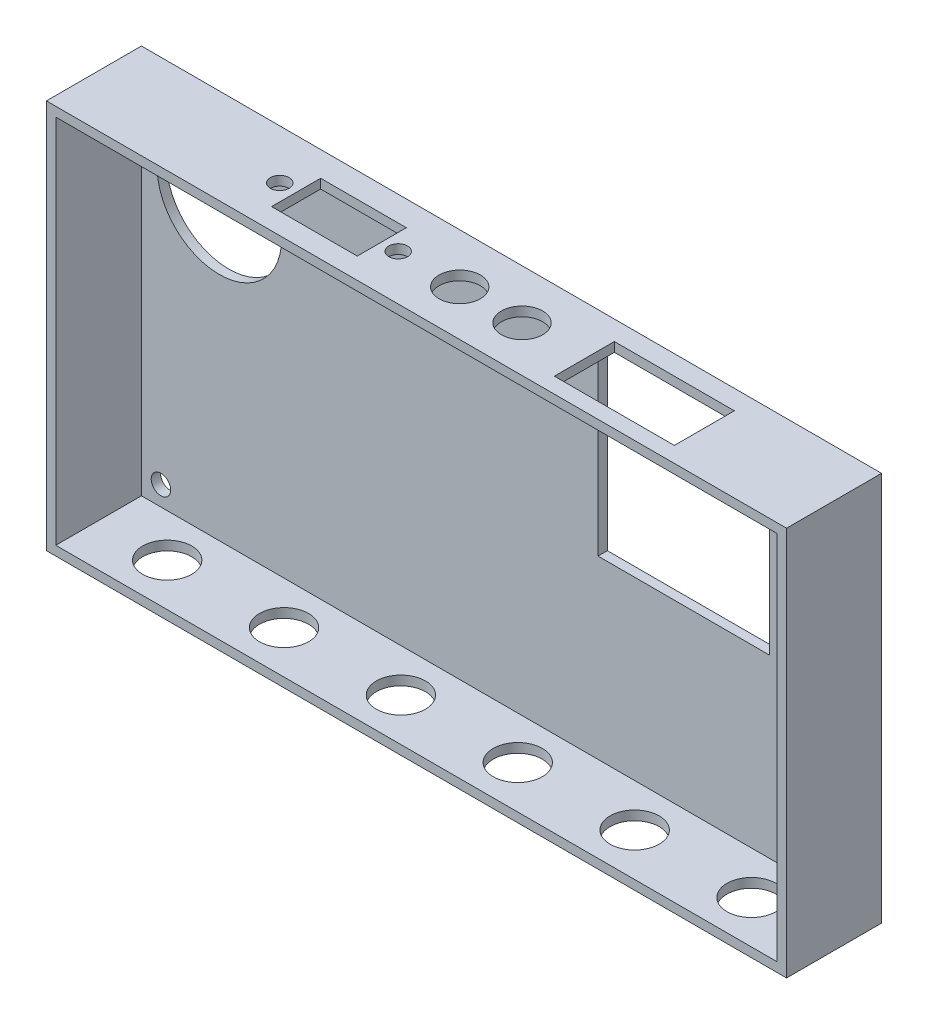
SolidWorks part; units mm, degrees
ref_plane "Přední rovina" through (0, 0, 0) normal (0, 0, 1) x (1, 0, 0)
ref_plane "Horní rovina" through (0, 0, 0) normal (0, 1, 0) x (1, 0, 0)
ref_plane "Pravá rovina" through (0, 0, 0) normal (1, 0, 0) x (0, 0, -1)
sketch "Skica2" plane through (0, 0, 1.2) normal (0, 0, 1) x (1, 0, 0)
  line L1 (0, 0) -> (95, 0)
  line L2 (0, 0) -> (0, -50)
  line L3 (0, -50) -> (95, -50)
  line L4 (95, 0) -> (95, -50)
  line L5 (1.2, -1.2) -> (93.8, -1.2)
  line L6 (1.2, -1.2) -> (1.2, -48.8)
  line L7 (1.2, -48.8) -> (93.8, -48.8)
  line L8 (93.8, -1.2) -> (93.8, -48.8)
  point P4 (-61.157, -16.9409)
  point P5 (-55.5801, -1.6845)
  point P10 (-58.1378, -9.6878)
  point P11 (31.0004, 46.0068)
  point P12 (0, 0)
  point P13 (-17.3487, 25.9803)
  point P14 (0, 0)
  point P15 (-82.3934, 59.2843)
  point P17 (-38.222, 35.8064)
  point P18 (-86.237, 24.8741)
  dimension "D1" = 90
  dimension "D2" = 95
  dimension "D3" = 1.2
  dimension "D4" = 1.2
  dimension "D5" = 1.2
  dimension "D6" = 1.2
  dimension "D7" = 50
extrude "Přidat vysunutím3" add sketch "Skica2" along normal blind 11 contours L2 L3 L4 L1
sketch "Skica7" plane through (45, -1.2, 0) normal (0, -1, 0) x (1, 0, 0)
  line L0 (-18.8, 6.35) -> (-7.8, 6.35) construction
  line L1 (-18.8, 3.2) -> (-7.8, 3.2)
  line L2 (-18.8, 3.2) -> (-18.8, 9.5)
  line L3 (-18.8, 9.5) -> (-7.8, 9.5)
  line L4 (-7.8, 3.2) -> (-7.8, 9.5)
  line L6 (-43.8, 12.2) -> (-43.8, 1.2) construction
  line L7 (48.8, 1.2) -> (-43.8, 1.2) construction
  circle A0 centre (-20.9, 6.35) radius 1.2
  circle A1 centre (-5.7, 6.35) radius 1.2
  point P8 (0, 0)
  point P11 (0, 0)
  point P12 (0, 0)
  point P13 (-13.3, 6.35)
  point P18 (15.1, 6.35)
  dimension "D4" = 2.4
  dimension "D5" = 2.4
  dimension "D1" = 11
  dimension "D2" = 6.3
  dimension "D3" = 15.2
  dimension "D6" = 7.6
  dimension "D7" = 2
  dimension "D8" = 25
extrude "Odebrat vysunutím1" cut sketch "Skica7" against normal through all
sketch "Skica8" plane through (45, -1.2, 0) normal (0, -1, 0) x (1, 0, 0)
  line L0 (-7.8, 6.35) -> (12.2, 6.35) construction
  line L1 (-7.8, 3.2) -> (-7.8, 9.5) construction
  line L2 (12.2, 6.35) -> (24.2, 6.35) construction
  line L3 (18.2, 2.5) -> (33.6, 2.5)
  line L4 (18.2, 2.5) -> (18.2, 10.2)
  line L5 (18.2, 10.2) -> (33.6, 10.2)
  line L6 (33.6, 2.5) -> (33.6, 10.2)
  circle A0 centre (2.2, 6.35) radius 2.65
  circle A1 centre (10.2, 6.35) radius 2.65
  point P8 (18.2, 6.35)
  dimension "D1" = 5.3
  dimension "D2" = 5.3
  dimension "D3" = 10
  dimension "D4" = 8
  dimension "D5" = 7.7
  dimension "D6" = 15.4
  dimension "D7" = 8
extrude "Odebrat vysunutím2" cut sketch "Skica8" against normal through all
sketch "Skica9" plane through (45, -50, 0) normal (0, -1, 0) x (1, 0, 0)
  line L0 (-35, 6.7) -> (40, 6.7) construction
  line L1 (2.5, 12.2) -> (2.5, 1.2) construction
  line L2 (-45, 12.2) -> (50, 12.2) construction
  line L3 (-45, 1.2) -> (50, 1.2) construction
  circle A0 centre (-35, 6.7) radius 3.15
  circle A1 centre (-20, 6.7) radius 3.15
  circle A2 centre (-5, 6.7) radius 3.15
  circle A3 centre (10, 6.7) radius 3.15
  circle A4 centre (25, 6.7) radius 3.15
  circle A5 centre (40, 6.7) radius 3.15
  point P18 (2.5, 6.7)
  point P19 (2.5, 6.7)
  point P20 (0, 0)
  dimension "D1" = 6.3
  dimension "D2" = 6.3
  dimension "D3" = 6.3
  dimension "D4" = 6.3
  dimension "D5" = 6.3
  dimension "D10" = 6.3
  dimension "D6" = 15
  dimension "D7" = 15
  dimension "D8" = 15
  dimension "D9" = 15
  dimension "D11" = 15
extrude "Odebrat vysunutím3" cut sketch "Skica9" against normal blind 15 contours A1 | A2 | A3 | A4 | A5 | A0
sketch "Skica12" plane through (0, 0, 1.2) normal (0, 0, -1) x (-1, 0, 0)
  line L1 (0, -50) -> (-95, -50)
  line L2 (0, -50) -> (0, 0)
  line L3 (0, 0) -> (-95, 0)
  line L4 (-95, -50) -> (-95, 0)
extrude "Přidat vysunutím4" add sketch "Skica12" along normal blind 1.2
sketch "Skica13" plane through (0, 0, 1.2) normal (0, 0, 1) x (1, 0, 0)
  line L1 (1.2, -1.2) -> (1.2, -48.8) construction
  line L2 (93.8, -1.2) -> (1.2, -1.2) construction
  line L3 (1.2, -48.8) -> (93.8, -48.8) construction
  line L4 (93.8, -48.8) -> (93.8, -1.2) construction
  line L6 (81.8, -1.2) -> (59.8, -1.2)
  line L7 (81.8, -1.2) -> (81.8, -26.2)
  line L8 (81.8, -26.2) -> (59.8, -26.2)
  line L9 (59.8, -1.2) -> (59.8, -26.2)
  circle A0 centre (3.7, -3.7) radius 1.2
  circle A1 centre (91.3, -46.3) radius 1.25
  circle A2 centre (11.2, -11.2) radius 8
  circle A3 centre (3.7, -46.3) radius 1.25
  circle A4 centre (91.3, -3.7) radius 1.25
  line M6 (93.8, -1.2) -> (1.2, -1.2)
  dimension "D1" = 2.4
  dimension "D6" = 2.5
  dimension "D7" = 2.5
  dimension "D8" = 2.5
  dimension "D9" = 16
  dimension "D2" = 2.5
  dimension "D3" = 2.5
  dimension "D4" = 2.5
  dimension "D5" = 2.5
  dimension "D10" = 10
  dimension "D11" = 10
  dimension "D12" = 22
  dimension "D13" = 25
  dimension "D14" = 12
extrude "Odebrat vysunutím4" cut sketch "Skica13" against normal blind 1.2 contours A2 | L9 L8 L7 M6 | A0 | A4 | A1 | A3
